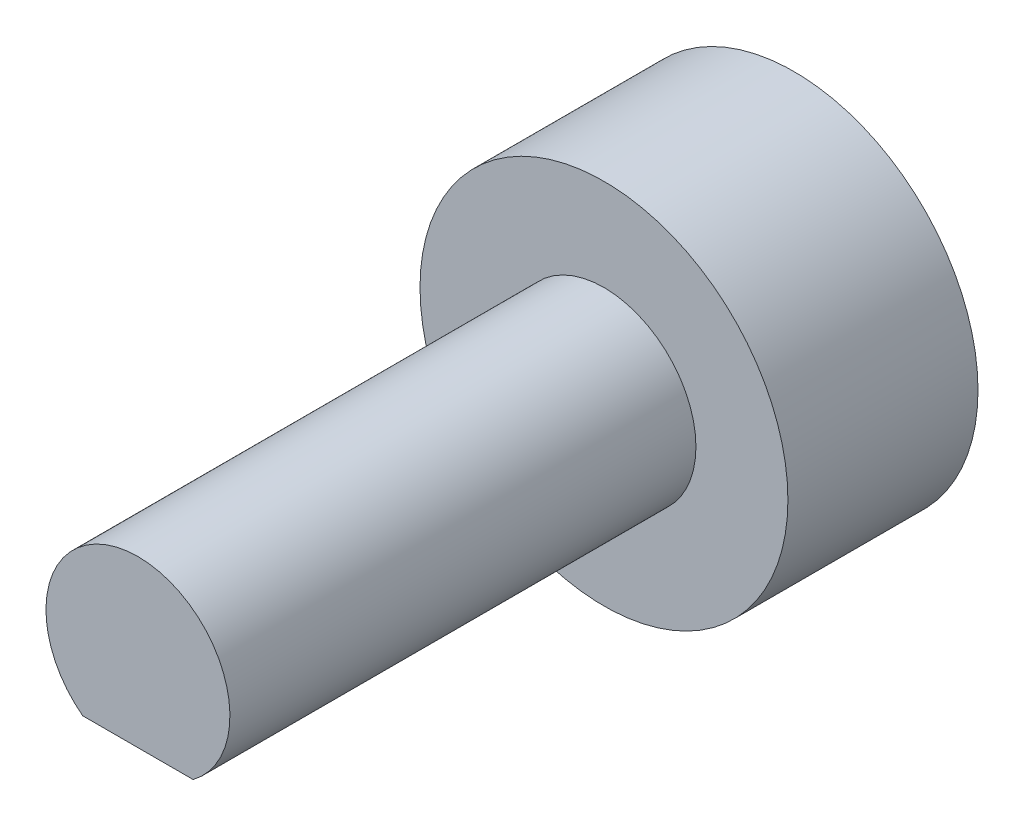
SolidWorks part; units mm, degrees
material "Fundición gris"
ref_plane "Alzado" through (0, 0, 0) normal (0, 0, 1) x (1, 0, 0)
ref_plane "Planta" through (0, 0, 0) normal (0, 1, 0) x (1, 0, 0)
ref_plane "Vista lateral" through (0, 0, 0) normal (1, 0, 0) x (0, 0, -1)
sketch "Croquis2" plane through (0, 0, 0) normal (0, 0, 1) x (1, 0, 0)
  circle A0 centre (0, 0) radius 6
  dimension "D1" = 12
extrude "Saliente-Extruir1" add sketch "Croquis2" against normal blind 6.2
sketch "Croquis3" plane through (0, 0, 0) normal (0, 0, 1) x (1, 0, 0)
  circle A0 centre (0, 0) radius 3
  dimension "D1" = 6
extrude "Saliente-Extruir2" add sketch "Croquis3" along normal blind 15.2
sketch "Croquis4" plane through (0, 0, 15.2) normal (0, 0, 1) x (1, 0, 0)
  line L0 (0, 3) -> (0, -2.4) construction
  line L1 (1.8, -2.4) -> (-1.8, -2.4)
  circle A0 centre (0, 0) radius 3 construction
  dimension "D1" = 5.4
extrude "Cortar-Extruir1" cut sketch "Croquis4" against normal blind 12.2 and the other way through all
